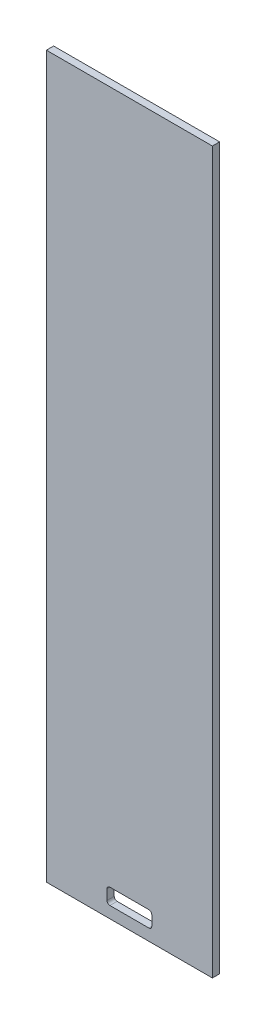
SolidWorks part; units mm, degrees
ref_plane "Front Plane" through (0, 0, 0) normal (0, 0, 1) x (1, 0, 0)
ref_plane "Top Plane" through (0, 0, 0) normal (0, 1, 0) x (1, 0, 0)
ref_plane "Right Plane" through (0, 0, 0) normal (1, 0, 0) x (0, 0, -1)
sketch "Sketch1" plane through (0, 0, 0) normal (0, 0, 1) x (1, 0, 0)
  line L0 (0, 0) -> (0, 607.3559) construction
  line L1 (-57.5, 499.2) -> (57.5, 499.2)
  line L2 (-57.5, 499.2) -> (-57.5, 0)
  line L3 (-57.5, 0) -> (57.5, 0)
  line L4 (57.5, 499.2) -> (57.5, 0)
  dimension "D1" = 499.2
  dimension "D2" = 115
extrude "Boss-Extrude1" add sketch "Sketch1" along normal blind 5
sketch "Sketch2" plane through (0, 0, 5) normal (0, 0, 1) x (1, 0, 0)
  line L0 (0, 0) -> (0, 190.7032) construction
  line L1 (-15.5, 19) -> (15.5, 19)
  line L2 (-15.5, 19) -> (-15.5, 8)
  line L3 (-15.5, 8) -> (15.5, 8)
  line L4 (15.5, 19) -> (15.5, 8)
  line L5 (-57.5, 0) -> (57.5, 0) construction
  dimension "D1" = 31
  dimension "D2" = 11
  dimension "D3" = 8
extrude "Cut-Extrude1" cut sketch "Sketch2" against normal up to next
fillet "Fillet1" radius 2 4 edges at (15.5, 8, 2.5) (15.5, 19, 2.5) (-15.5, 8, 2.5) (-15.5, 19, 2.5)
